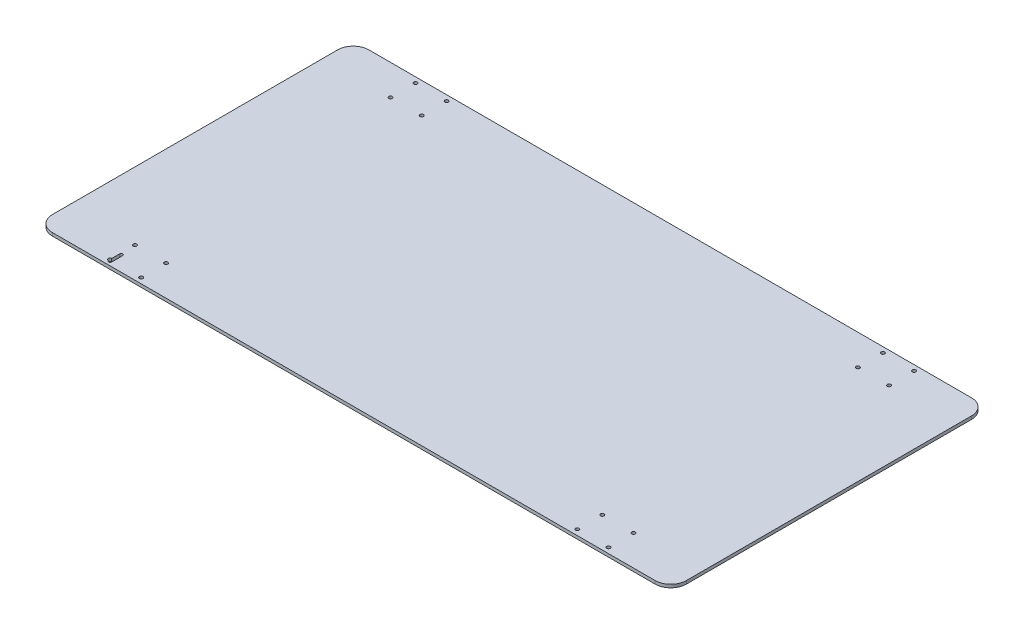
SolidWorks part; units mm, degrees
ref_plane "Front Plane" through (0, 0, 0) normal (0, 0, 1) x (1, 0, 0)
ref_plane "Top Plane" through (0, 0, 0) normal (0, 1, 0) x (1, 0, 0)
ref_plane "Right Plane" through (0, 0, 0) normal (1, 0, 0) x (0, 0, -1)
sketch "Sketch1" plane through (0, 0, 0) normal (0, 1, 0) x (1, 0, 0)
  line L1 (-304.5, 152) -> (304.5, 152)
  line L2 (-304.5, 152) -> (-304.5, -152)
  line L3 (-304.5, -152) -> (304.5, -152)
  line L4 (304.5, 152) -> (304.5, -152)
  line L5 (-304.5, 152) -> (304.5, -152) construction
  line L6 (-304.5, -152) -> (304.5, 152) construction
  circle A0 centre (-239.5, 146.762) radius 1.7
  circle A1 centre (-209.5, 146.762) radius 1.7
  circle A2 centre (-209.5, 122.762) radius 1.7
  circle A3 centre (-239.5, 122.762) radius 1.7
  circle A4 centre (-239.5, -122.762) radius 1.7
  circle A5 centre (-209.5, -122.762) radius 1.7
  circle A6 centre (-209.5, -146.762) radius 1.7
  circle A7 centre (-239.5, -146.762) radius 1.7
  circle A8 centre (209.5, -122.762) radius 1.7
  circle A9 centre (239.5, -122.762) radius 1.7
  circle A10 centre (239.5, -146.762) radius 1.7
  circle A11 centre (209.5, -146.762) radius 1.7
  circle A12 centre (209.5, 146.762) radius 1.7
  circle A13 centre (239.5, 146.762) radius 1.7
  circle A14 centre (239.5, 122.762) radius 1.7
  circle A15 centre (209.5, 122.762) radius 1.7
  point P0 (0, 0)
  dimension "D1" = 304
  dimension "D2" = 609
extrude "Boss-Extrude1" add sketch "Sketch1" along normal blind 3
fillet "Fillet1" radius 15 4 edges at (-304.5, 1.5, 152) (-304.5, 1.5, -152) (304.5, 1.5, -152) (304.5, 1.5, 152)
sketch "Sketch2" plane through (0, 0, 0) normal (0, -1, 0) x (-1, 0, 0)
  line L0 (244.5, -152) -> (244.5, 152) construction
  line L1 (289.5, -152) -> (-289.5, -152) construction
  line L2 (-289.5, 152) -> (289.5, 152) construction
  line L3 (-244.5, -152) -> (-244.5, 152) construction
  line L4 (304.5, 137) -> (304.5, -137) construction
  line L5 (-304.5, -137) -> (-304.5, 137) construction
  dimension "D1" = 60
  dimension "D2" = 60
sketch "Sketch3" plane through (0, 3, 0) normal (0, 1, 0) x (1, 0, 0)
  line L0 (-238, -137.5) -> (-238, -148) construction
  line L1 (-236.5, -137.5) -> (-236.5, -148)
  line L2 (-239.5, -137.5) -> (-239.5, -148)
  line L3 (-289.5, -152) -> (289.5, -152) construction
  line L4 (-244.5, -152) -> (-244.5, 152) construction
  arc A0 (-236.5, -137.5) -> (-239.5, -137.5) centre (-238, -137.5) ccw
  arc A1 (-239.5, -148) -> (-236.5, -148) centre (-238, -148) ccw
  point P2 (-238, -142.75)
  point P8 (-238, -136)
  point P9 (-238, -149.5)
  dimension "D1" = 12
  dimension "D2" = 3
  dimension "D3" = 2.5
  dimension "D4" = 5
extrude "Cut-Extrude1" cut sketch "Sketch3" against normal through all
